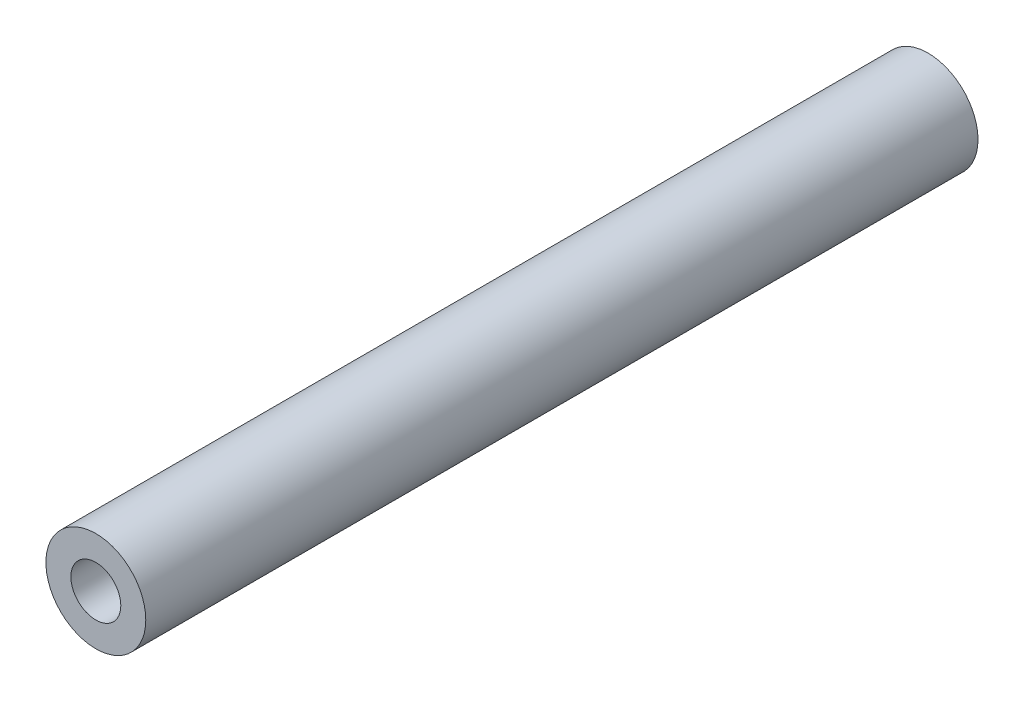
SolidWorks part; units mm, degrees
ref_plane "前视基准面" through (0, 0, 0) normal (0, 0, 1) x (1, 0, 0)
ref_plane "上视基准面" through (0, 0, 0) normal (0, 1, 0) x (1, 0, 0)
ref_plane "右视基准面" through (0, 0, 0) normal (1, 0, 0) x (0, 0, -1)
sketch "Sketch1" plane through (0, 0, 0) normal (0, 0, 1) x (1, 0, 0)
  circle A0 centre (0, 0) radius 6
  circle A1 centre (0, 0) radius 3
extrude "Boss-Extrude1" add sketch "Sketch1" along normal blind 100
